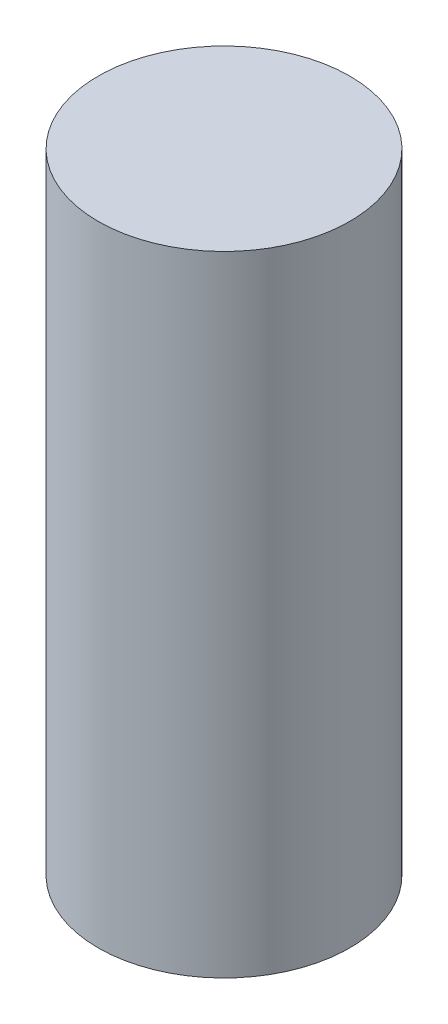
SolidWorks part; units mm, degrees
ref_plane "Front Plane" through (0, 0, 0) normal (0, 0, 1) x (1, 0, 0)
ref_plane "Top Plane" through (0, 0, 0) normal (0, 1, 0) x (1, 0, 0)
ref_plane "Right Plane" through (0, 0, 0) normal (1, 0, 0) x (0, 0, -1)
sketch "Sketch1" plane through (0, 0, 0) normal (0, 1, 0) x (1, 0, 0)
  circle A0 centre (0, 0) radius 20
extrude "Boss-Extrude1" add sketch "Sketch1" along normal blind 100
